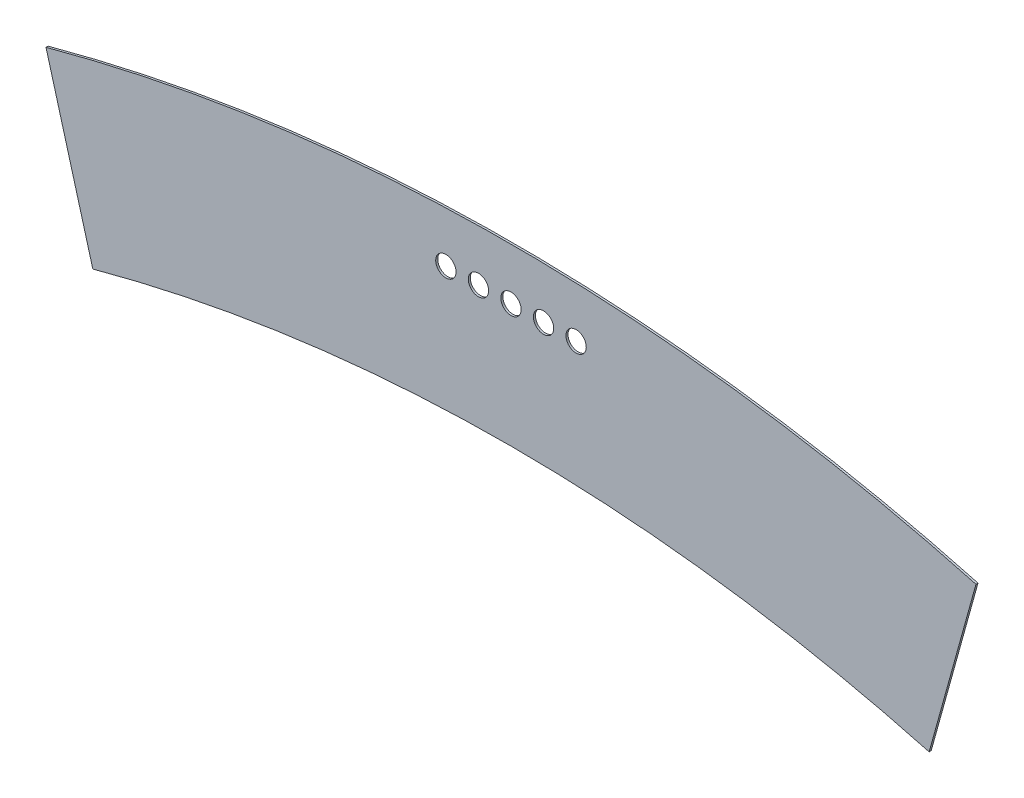
SolidWorks part; units mm, degrees
material "6061 Alloy"
ref_plane "front" through (0, 0, 0) normal (0, 0, 1) x (1, 0, 0)
ref_plane "top" through (0, 0, 0) normal (0, 1, 0) x (1, 0, 0)
ref_plane "right" through (0, 0, 0) normal (1, 0, 0) x (0, 0, -1)
sketch "Sketch1" plane through (0, 0, 0) normal (0, 0, 1) x (1, 0, 0)
  line L0 (0, 0) -> (0, -273.05) construction
  line L1 (0, 0) -> (83.8667, 0) construction
  line L2 (-725.551, -96.9263) -> (-652.5006, -360.0274)
  line L3 (725.551, -96.9263) -> (652.5006, -360.0274)
  arc A0 (725.551, -96.9263) -> (-725.551, -96.9263) centre (0, -2764.0534) ccw
  arc A1 (652.5006, -360.0274) -> (-652.5006, -360.0274) centre (0, -2764.0534) ccw
  circle A2 centre (0, -80.7212) radius 15.875
  circle A3 centre (-50.8, -80.7212) radius 15.875
  circle A4 centre (-101.6, -80.7212) radius 15.875
  circle A5 centre (50.8, -80.7212) radius 15.875
  circle A6 centre (101.6, -80.7212) radius 15.875
  dimension "D1" = 2764.0534
  dimension "D5" = 31.75
  dimension "D2" = 1451.102
  dimension "D3" = 273.05
  dimension "D4" = 652.5006
  dimension "D6" = 80.7212
  dimension "D7" = 50.8
  dimension "D8" = 50.8
  dimension "D9" = 50.8
  dimension "D10" = 50.8
  dimension "D11" = 725.551
  dimension "D13" = 652.5006
extrude "Base-Extrude" add sketch "Sketch1" against normal blind 3.175
